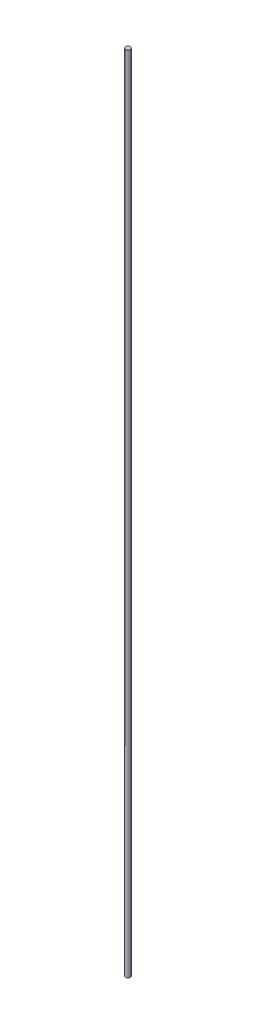
SolidWorks part; units mm, degrees
material "Plain Carbon Steel"
ref_plane "Front Plane" through (0, 0, 0) normal (0, 0, 1) x (1, 0, 0)
ref_plane "Top Plane" through (0, 0, 0) normal (0, 1, 0) x (1, 0, 0)
ref_plane "Right Plane" through (0, 0, 0) normal (1, 0, 0) x (0, 0, -1)
sketch "Sketch1" plane through (0, 0, 0) normal (0, 1, 0) x (1, 0, 0)
  circle A0 centre (0, 0) radius 6
  dimension "D1" = 12
extrude "Boss-Extrude1" add sketch "Sketch1" along normal blind 2000
